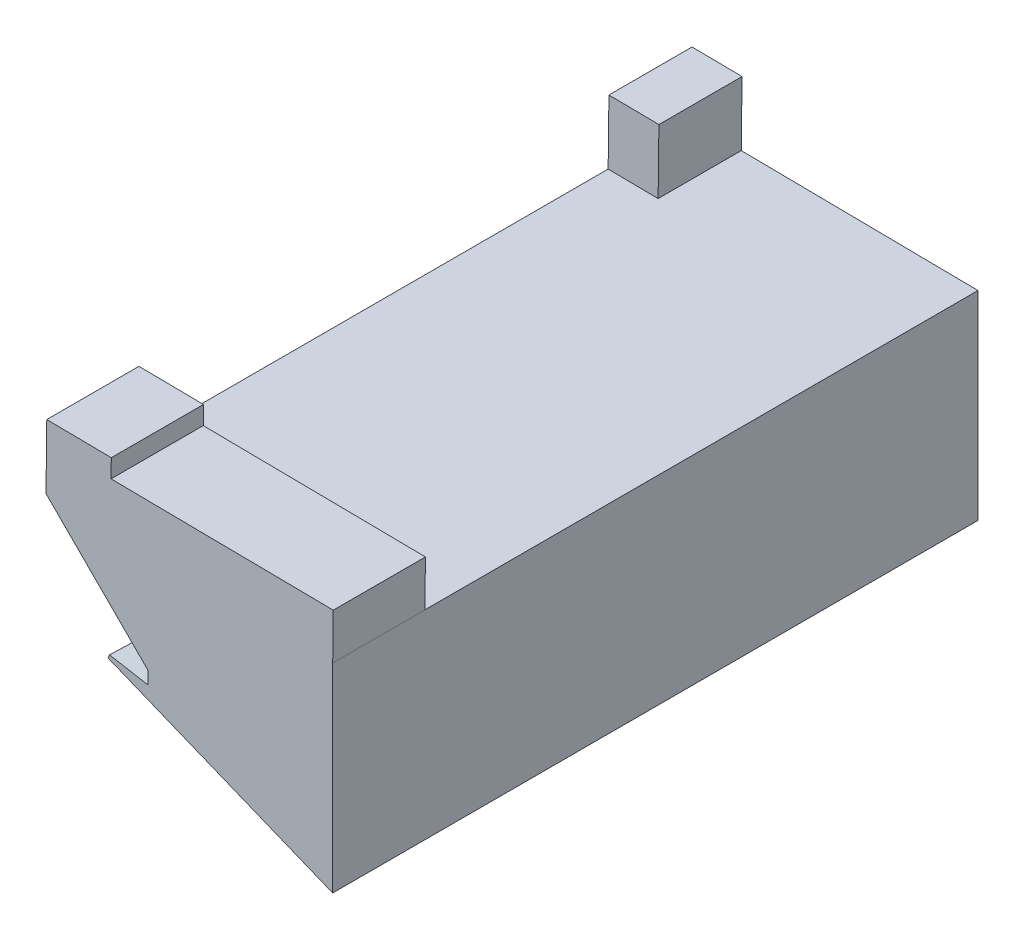
SolidWorks part; units mm, degrees
ref_plane "Plan de face" through (0, 0, 0) normal (0, 0, 1) x (1, 0, 0)
ref_plane "Plan de dessus" through (0, 0, 0) normal (0, 1, 0) x (1, 0, 0)
ref_plane "Plan de droite" through (0, 0, 0) normal (1, 0, 0) x (0, 0, -1)
sketch "Esquisse1" plane through (0, 0, 0) normal (0, 0, 1) x (1, 0, 0)
  line L1 (0, -0.6382) -> (-5.5317, 4.8936)
  line L2 (-5.5317, 4.8936) -> (10.0186, 4.7096)
  line L7 (0, 0) -> (14.219, 0) construction
  line L8 (10.0186, 4.7096) -> (10.0169, -6.0927)
  line L10 (0, -1.3268) -> (0, -0.6382)
  line L11 (-3.0321, -0.7922) -> (10.0169, -6.0927)
  line L12 (0, -1.3268) -> (-3.0321, -0.7922)
  point P8 (10.0169, 0.7096)
  point P10 (10.0169, -6.0927)
  point P11 (0, 0)
  point P12 (0, 0)
  dimension "D1" = 4
  dimension "D2" = 45
  dimension "D4" = 15.5503
extrude "Boss.-Extru.1" add sketch "Esquisse1" along normal blind 35
sketch "Esquisse3" plane through (0.0571, 4.8274, 0) normal (0.0118, 0.9999, 0) x (0.9999, -0.0118, 0)
  line L0 (9.9622, -35) -> (9.9622, -30)
  line L1 (9.9622, -35) -> (9.9622, 0) construction
  line L2 (9.9622, -30) -> (-5.5892, -30)
  line L3 (-5.5892, -35) -> (-5.5892, 0) construction
  line L4 (-5.5892, -30) -> (-5.5892, -35)
  line L5 (9.9622, -35) -> (-5.5892, -35) construction
  line L6 (-5.5892, -35) -> (9.9622, -35)
  dimension "D1" = 5
extrude "Boss.-Extru.3" add sketch "Esquisse3" along normal blind 3.5
ref_plane "Plan1" through (0.2168, 18.3265, 0) normal (0.0118, 0.9999, 0) x (0.9999, -0.0118, 0)
sketch "Esquisse4" plane through (0.2168, 18.3265, 0) normal (0.0118, 0.9999, 0) x (0.9999, -0.0118, 0)
  line L1 (-2.0892, -28.5941) -> (12.9009, -28.5941)
  line L2 (-2.0892, -28.5941) -> (-2.0892, -37.1372)
  line L3 (-2.0892, -37.1372) -> (12.9009, -37.1372)
  line L4 (12.9009, -28.5941) -> (12.9009, -37.1372)
  line L5 (-2.0892, -28.5941) -> (12.9009, -37.1372) construction
  line L6 (-2.0892, -37.1372) -> (12.9009, -28.5941) construction
  point P0 (5.4058, -32.8656)
  dimension "D1" = 3.5
extrude "Enlèv. mat.-Extru.4" cut sketch "Esquisse4" against normal blind 11
sketch "Esquisse5" plane through (0.0571, 4.8274, 0) normal (0.0118, 0.9999, 0) x (0.9999, -0.0118, 0)
  line L0 (9.9622, 0) -> (-5.5892, 0) construction
  line L1 (-5.5892, 0) -> (-2.8781, 0)
  line L2 (-5.5892, 0) -> (-5.5892, -4.5099)
  line L3 (-5.5892, -4.5099) -> (-2.8781, -4.5099)
  line L4 (-2.8781, 0) -> (-2.8781, -4.5099)
extrude "Boss.-Extru.4" add sketch "Esquisse5" along normal blind 3.5
fillet "Congé2" radius 0.1 1 edges at (-3.0321, -0.7922, 17.5)
ref_plane "Plan2" through (-4.469, -11.002, 0) normal (-0.3763, -0.9265, 0) x (-0.9265, 0.3763, 0)
sketch "Esquisse6" plane through (-4.469, -11.002, 0) normal (-0.3763, -0.9265, 0) x (-0.9265, 0.3763, 0)
  line L0 (1.6753, 0.4927) -> (1.6753, -38.4613)
  line L1 (1.6753, -38.4613) -> (0.5321, 0.4927)
  line L2 (0.5321, 0.4927) -> (1.6753, 0.4927)
  point P2 (-0.5545, 0.394)
  point P4 (1.8662, 0.504)
  point P5 (0.719, 0.504)
  point P6 (2.3419, -40.9391)
  point P7 (0, 0)
  point P8 (0, 0)
  point P9 (0, 0)
  point P10 (3.0162, -37.6778)
  point P11 (0, 0)
  point P12 (0, 0)
  point P13 (-0.8212, 0.7708)
  point P14 (0, 0)
  point P15 (0, 0)
  point P16 (2.141, -37.7374)
  point P17 (0, 0)
  point P18 (0, 0)
  point P19 (1.6753, -38.4613)
  point P20 (0, 0)
  point P21 (0, 0)
  point P22 (0, 0)
  point P23 (0, 0)
  point P24 (0, 0)
  point P25 (0.5321, 0.4927)
extrude "Enlèv. mat.-Extru.7" cut sketch "Esquisse6" against normal blind 11
